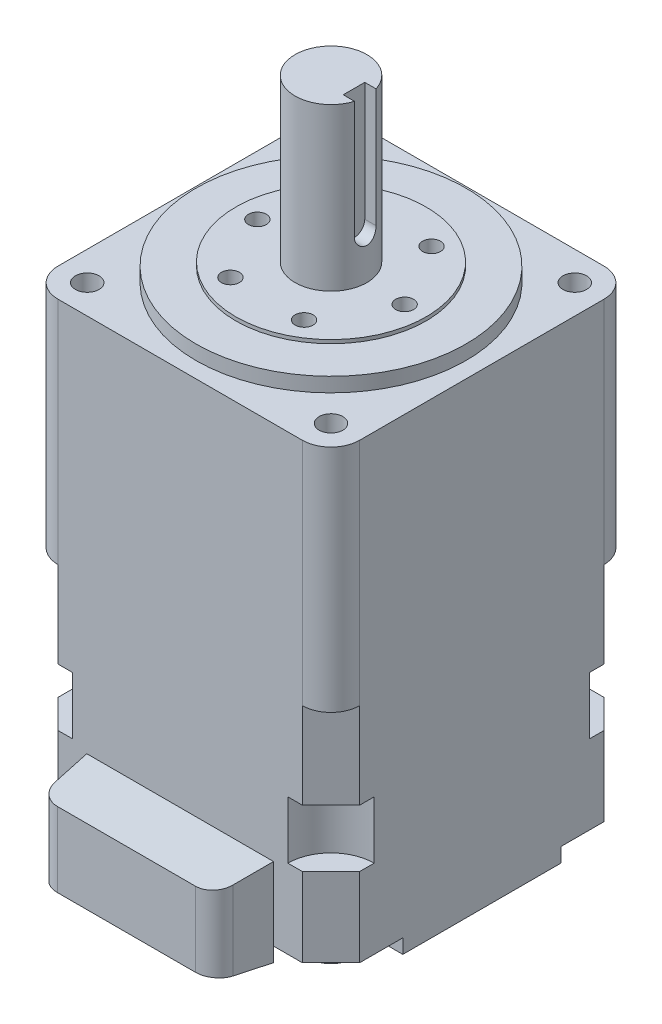
SolidWorks part; units mm, degrees
ref_plane "前视基准面" through (0, 0, 0) normal (0, 0, 1) x (1, 0, 0)
ref_plane "上视基准面" through (0, 0, 0) normal (0, 1, 0) x (1, 0, 0)
ref_plane "右视基准面" through (0, 0, 0) normal (1, 0, 0) x (0, 0, -1)
other "Configuration Table"
sketch "草图1" plane through (0, 0, 0) normal (0, 1, 0) x (1, 0, 0)
  line L1 (17, -21) -> (-17, -21)
  line L2 (21, -17) -> (21, 17)
  line L3 (17, 21) -> (-17, 21)
  line L4 (-21, -17) -> (-21, 17)
  line L5 (21, -21) -> (-21, 21) construction
  line L6 (21, 21) -> (-21, -21) construction
  arc A0 (-21, -17) -> (-17, -21) centre (-17, -17) ccw
  arc A1 (17, -21) -> (21, -17) centre (17, -17) ccw
  arc A2 (21, 17) -> (17, 21) centre (17, 17) ccw
  arc A3 (-17, 21) -> (-21, 17) centre (-17, 17) ccw
  point P0 (0, 0)
  dimension "D3" = 4
  dimension "D1" = 42
  dimension "D2" = 42
extrude "凸台-拉伸1" add sketch "草图1" along normal blind 65
sketch "草图2" plane through (0, 0, 0) normal (0, -1, 0) x (1, 0, 0)
  line L0 (-17, 21) -> (-21, 17)
  line L1 (17, 21) -> (21, 17)
  line L2 (-21, -17) -> (-17, -21)
  line L4 (21, -17) -> (17, -21)
  arc A0 (-21, -17) -> (-17, -21) centre (-17, -17) ccw construction
  arc A1 (17, -21) -> (21, -17) centre (17, -17) ccw construction
  arc A2 (21, 17) -> (17, 21) centre (17, 17) ccw construction
  arc A3 (-17, 21) -> (-21, 17) centre (-17, 17) ccw construction
  arc A4 (-21, -17) -> (-17, -21) centre (-17, -17) ccw
  arc A5 (17, -21) -> (21, -17) centre (17, -17) ccw
  arc A6 (21, 17) -> (17, 21) centre (17, 17) ccw
  arc A7 (-17, 21) -> (-21, 17) centre (-17, 17) ccw
extrude "切除-拉伸1" cut sketch "草图2" against normal blind 33
sketch "草图3" plane through (0, 0, 0) normal (0, -1, 0) x (1, 0, 0)
  line L0 (-21, -17) -> (-21, 17) construction
  line L1 (-17, 21) -> (17, 21) construction
  line L2 (0, 29.1197) -> (0, 0) construction
  line L3 (0, 0) -> (26.2848, 0) construction
  line L4 (-21, 15) -> (-21, 21)
  line L5 (-21, 21) -> (-15, 21)
  line L6 (21, 21) -> (15, 21)
  line L7 (21, 15) -> (21, 21)
  line L8 (-21, -21) -> (-15, -21)
  line L9 (-21, -15) -> (-21, -21)
  line L10 (21, -15) -> (21, -21)
  line L11 (21, -21) -> (15, -21)
  arc A0 (-21, 15) -> (-15, 21) centre (-21, 21) ccw
  arc A1 (21, 15) -> (15, 21) centre (21, 21) cw
  arc A2 (-21, -15) -> (-15, -21) centre (-21, -21) cw
  arc A3 (21, -15) -> (15, -21) centre (21, -21) ccw
  dimension "D1" = 6
extrude "切除-拉伸2" cut sketch "草图3" against normal blind 8 from offset 13 offset against normal yes
sketch "草图4" plane through (0, 0, 0) normal (0, -1, 0) x (1, 0, 0)
  line L1 (-21, 21) -> (-11, 21)
  line L2 (-21, 21) -> (-21, 11)
  line L3 (-21, 11) -> (-16, 11)
  line L4 (-11, 21) -> (-11, 16)
  line L5 (-17, 21) -> (17, 21) construction
  line L6 (-21, -17) -> (-21, 17) construction
  line L7 (0, 0) -> (0, 27.1513) construction
  line L8 (0, 0) -> (31.2575, 0) construction
  line L9 (11, 21) -> (11, 16)
  line L10 (21, 11) -> (16, 11)
  line L11 (21, 21) -> (21, 11)
  line L12 (21, 21) -> (11, 21)
  line L13 (-11, -21) -> (-11, -16)
  line L14 (-21, -11) -> (-16, -11)
  line L15 (-21, -21) -> (-21, -11)
  line L16 (-21, -21) -> (-11, -21)
  line L17 (21, -21) -> (11, -21)
  line L18 (21, -21) -> (21, -11)
  line L19 (21, -11) -> (16, -11)
  line L20 (11, -21) -> (11, -16)
  arc A0 (-16, 11) -> (-11, 16) centre (-16, 16) ccw
  arc A1 (16, 11) -> (11, 16) centre (16, 16) cw
  arc A2 (-16, -11) -> (-11, -16) centre (-16, -16) cw
  arc A3 (16, -11) -> (11, -16) centre (16, -16) ccw
  point P10 (-11, 11)
  point P21 (11, 11)
  point P28 (-11, -11)
  point P35 (11, -11)
  dimension "D3" = 5
  dimension "D1" = 10
  dimension "D2" = 10
extrude "切除-拉伸3" cut sketch "草图4" against normal blind 2
sketch "草图5" plane through (0, 2, 0) normal (0, -1, 0) x (1, 0, 0)
  line L1 (15.5, -15.5) -> (-15.5, -15.5) construction
  line L2 (15.5, -15.5) -> (15.5, 15.5) construction
  line L3 (15.5, 15.5) -> (-15.5, 15.5) construction
  line L4 (-15.5, -15.5) -> (-15.5, 15.5) construction
  line L5 (15.5, -15.5) -> (-15.5, 15.5) construction
  line L6 (15.5, 15.5) -> (-15.5, -15.5) construction
  circle A1 centre (-15.5, 15.5) radius 3
  circle A2 centre (15.5, 15.5) radius 3
  circle A3 centre (15.5, -15.5) radius 3
  circle A4 centre (-15.5, -15.5) radius 3
  point P0 (0, 0)
  dimension "D3" = 6
  dimension "D1" = 31
  dimension "D2" = 31
extrude "凸台-拉伸2" add sketch "草图5" along normal blind 1.5
sketch "草图6" plane through (0, 0, 21) normal (0, 0, 1) x (1, 0, 0)
  line L0 (-11, 0) -> (11, 0) construction
  line L1 (-13, 0) -> (13, 0)
  line L2 (-13, 0) -> (-13, 12.2)
  line L3 (-13, 12.2) -> (13, 12.2)
  line L4 (13, 0) -> (13, 12.2)
  line L5 (0, 0) -> (0, 16.7017) construction
  dimension "D1" = 12.2
  dimension "D2" = 26
extrude "凸台-拉伸3" add sketch "草图6" along normal blind 7.5
sketch "草图7" plane through (-13, 0, 0) normal (-1, 0, 0) x (0, 0, 1)
  line L0 (21, 12.2) -> (28.5, 11.2924)
  line L1 (28.5, 12.2) -> (28.5, 0) construction
  line L2 (21, 13) -> (21, 2) construction
  line L3 (28.5, 12.2) -> (21, 12.2) construction
  line L4 (28.5, 12.2) -> (21, 12.2)
  line L5 (28.5, 12.2) -> (28.5, 11.2924)
  line L6 (28.5, 6.1) -> (23.5388, 6.1) construction
  line L7 (28.5, 0) -> (28.5, 0.9076)
  line L8 (28.5, 0) -> (21, 0)
  line L9 (21, 0) -> (28.5, 0.9076)
  dimension "D1" = 83.1
extrude "切除-拉伸4" cut sketch "草图7" against normal up to next
sketch "草图9" plane through (0, 0, 0) normal (0, -1, 0) x (1, 0, 0)
  line L0 (-13, 21) -> (-12.0924, 28.5)
  line L1 (13, 28.5) -> (-13, 28.5) construction
  line L2 (-12.0924, 28.5) -> (-13, 28.5)
  line L3 (-13, 28.5) -> (-13, 21)
  line L4 (0, 21) -> (0, 31.724) construction
  line L5 (11, 21) -> (-11, 21) construction
  line L6 (-13, 21) -> (-11, 21) construction
  line L7 (13, 28.5) -> (13, 21)
  line L8 (12.0924, 28.5) -> (13, 28.5)
  line L9 (13, 21) -> (12.0924, 28.5)
  dimension "D1" = 83.1
extrude "切除-拉伸5" cut sketch "草图9" against normal up to next
fillet "圆角2" radius 2.8 2 edges at (12.0924, 6.1, 28.5) (-12.0924, 6.1, 28.5)
sketch "草图10" plane through (0, 65, 0) normal (0, 1, 0) x (1, 0, 0)
  circle A0 centre (0, 0) radius 18.8
  dimension "D1" = 37.6
extrude "凸台-拉伸4" add sketch "草图10" along normal blind 2
sketch "草图11" plane through (0, 67, 0) normal (0, 1, 0) x (1, 0, 0)
  circle A0 centre (0, 0) radius 13.25
  dimension "D1" = 26.5
extrude "凸台-拉伸5" add sketch "草图11" along normal blind 0.5
sketch "草图12" plane through (0, 67.5, 0) normal (0, 1, 0) x (1, 0, 0)
  circle A0 centre (0, 0) radius 5
  dimension "D1" = 10
extrude "凸台-拉伸6" add sketch "草图12" along normal blind 22.5
sketch "草图13" plane through (0, 0, 0) normal (1, 0, 0) x (0, 0, -1)
  line L0 (0, 91.6844) -> (0, 61.348) construction
  line L1 (0, 90) -> (0, 73.5) construction
  line L2 (5, 90) -> (-5, 90) construction
  line L3 (1.5, 90) -> (1.5, 73.5)
  line L4 (-1.5, 90) -> (-1.5, 73.5)
  arc A0 (1.5, 90) -> (-1.5, 90) centre (0, 90) ccw
  arc A1 (-1.5, 73.5) -> (1.5, 73.5) centre (0, 73.5) ccw
  point P7 (0, 81.75)
  dimension "D1" = 3
  dimension "D2" = 16.5
extrude "切除-拉伸6" cut sketch "草图13" along normal up to next from offset 3.2
hole_wizard "M3 螺纹孔2" positions "草图17" profile "草图18" tap size "M3" standard "GB"
sketch "草图17" plane through (0, 67.5, 0) normal (0, 1, 0) x (1, 0, 0)
  line L1 (0, 0) -> (14.5994, 0) construction
  circle A0 centre (0, 0) radius 10.25 construction
  point P14 (10.25, 0)
  point P21 (5.125, -8.8768)
  point P22 (-5.125, -8.8768)
  point P23 (-10.25, 0)
  point P24 (-5.125, 8.8768)
  point P25 (5.125, 8.8768)
  dimension "D1" = 20.5
  dimension "D2" = 6
sketch "草图18" plane through (5.125, 67.5, -8.8768) normal (1, 0, 0) x (0, 0, 1)
  line L0 (0, 0) -> (0, 7.2511)
  line L1 (0, 7.2511) -> (1.25, 6.5)
  line L2 (1.25, 6.5) -> (1.25, 0)
  line L5 (1.25, 0) -> (0, 0)
  line L10 (0, 7.2511) -> (-1.25, 6.5) construction
  line L11 (0, -6.35) -> (0, 107.95) construction
  dimension "螺纹孔钻头直径" = 2.5
  dimension "螺纹孔钻头深度" = 6.5
  dimension "导头角度" = 118
cosmetic thread "孔螺蚊线7" parameters "D1"=5, "D2"=3
cosmetic thread "孔螺蚊线8" parameters "D1"=5, "D2"=3
cosmetic thread "孔螺蚊线9" parameters "D1"=5, "D2"=3
cosmetic thread "孔螺蚊线10" parameters "D1"=5, "D2"=3
cosmetic thread "孔螺蚊线11" parameters "D1"=5, "D2"=3
cosmetic thread "孔螺蚊线12" parameters "D1"=5, "D2"=3
hole_wizard "M4 螺纹孔1" positions "草图19" profile "草图20" tap size "M4" standard "GB"
sketch "草图19" plane through (0, 65, 0) normal (0, 1, 0) x (1, 0, 0)
  line L1 (16.9706, -16.9706) -> (-16.9706, -16.9706) construction
  line L2 (16.9706, -16.9706) -> (16.9706, 16.9706) construction
  line L3 (16.9706, 16.9706) -> (-16.9706, 16.9706) construction
  line L4 (-16.9706, -16.9706) -> (-16.9706, 16.9706) construction
  line L5 (16.9706, -16.9706) -> (-16.9706, 16.9706) construction
  line L6 (16.9706, 16.9706) -> (-16.9706, -16.9706) construction
  circle A0 centre (0, 0) radius 24 construction
  point P7 (-16.9706, 16.9706)
  point P126 (16.9706, -16.9706)
  point P127 (16.9706, 16.9706)
  point P128 (-16.9706, -16.9706)
  point P138 (-16.9706, 16.9706)
  point P140 (16.9706, 16.9706)
  point P142 (16.9706, -16.9706)
  point P144 (-16.9706, -16.9706)
  dimension "D1" = 48
sketch "草图20" plane through (-16.9706, 65, 16.9706) normal (1, 0, 0) x (0, 0, 1)
  line L0 (0, 0) -> (0, 10.9914)
  line L1 (0, 10.9914) -> (1.65, 10)
  line L2 (1.65, 10) -> (1.65, 0)
  line L5 (1.65, 0) -> (0, 0)
  line L10 (0, 10.9914) -> (-1.65, 10) construction
  line L11 (0, -6.35) -> (0, 107.95) construction
  dimension "螺纹孔钻头直径" = 3.3
  dimension "螺纹孔钻头深度" = 10
  dimension "导头角度" = 118
cosmetic thread "孔螺蚊线13" parameters "D1"=8, "D2"=4
cosmetic thread "孔螺蚊线14" parameters "D1"=8, "D2"=4
cosmetic thread "孔螺蚊线15" parameters "D1"=8, "D2"=4
cosmetic thread "孔螺蚊线16" parameters "D1"=8, "D2"=4
